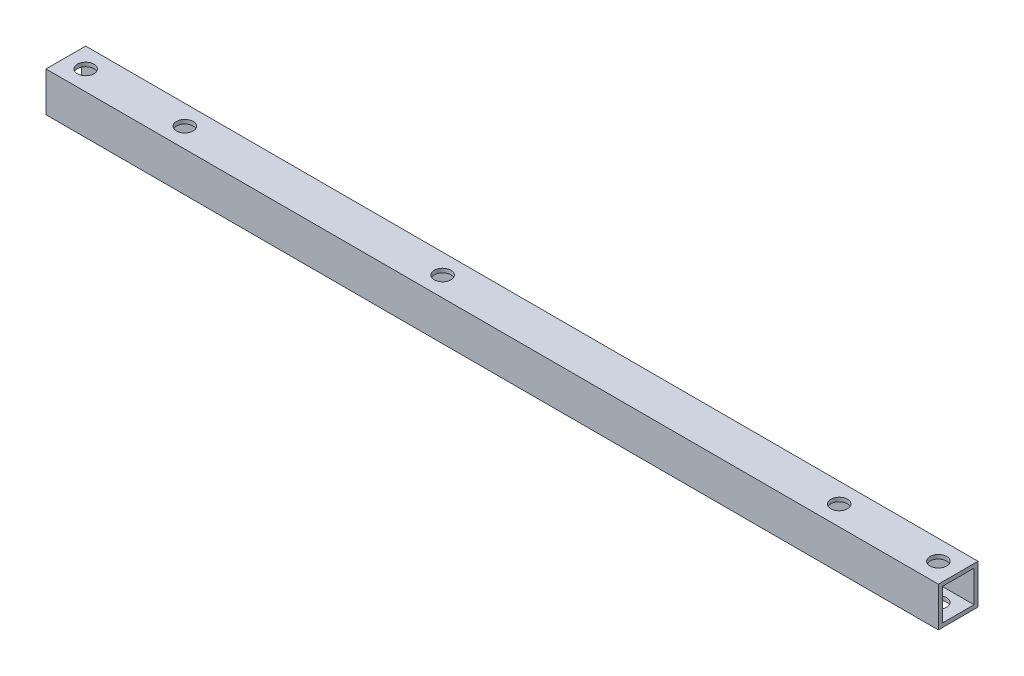
SolidWorks part; units mm, degrees
material "5052-H34"
ref_plane "正面" through (0, 0, 0) normal (0, 0, 1) x (1, 0, 0)
ref_plane "平面" through (0, 0, 0) normal (0, 1, 0) x (1, 0, 0)
ref_plane "右側面" through (0, 0, 0) normal (1, 0, 0) x (0, 0, -1)
sketch "ｽｹｯﾁ1" plane through (0, 0, 0) normal (1, 0, 0) x (0, 0, -1)
  line L1 (-5, 5) -> (5, 5)
  line L2 (-5, 5) -> (-5, -5)
  line L3 (-5, -5) -> (5, -5)
  line L4 (5, 5) -> (5, -5)
  line L5 (-5, 5) -> (5, -5) construction
  line L6 (-5, -5) -> (5, 5) construction
  point P0 (0, 0)
  dimension "D1" = 10
extrude "押し出し-薄板1" add sketch "ｽｹｯﾁ1" along normal blind 225 thin
sketch "ｽｹｯﾁ2" plane through (0, 5, 0) normal (0, 1, 0) x (1, 0, 0)
  line L0 (225, 0) -> (195, 0) construction
  line L1 (225, 5) -> (225, -5) construction
  line L2 (112.5, 5) -> (112.5, -5) construction
  line L3 (225, 5) -> (0, 5) construction
  line L4 (225, -5) -> (0, -5) construction
  line L5 (0, 0) -> (30, 0) construction
  circle A0 centre (195, 0) radius 2.1
  circle A1 centre (220, 0) radius 2.1
  circle A2 centre (5, 0) radius 2.1
  circle A3 centre (30, 0) radius 2.1
  dimension "D1" = 4.2
  dimension "D2" = 25
  dimension "D3" = 5
extrude "ｶｯﾄ - 押し出し1" cut sketch "ｽｹｯﾁ2" against normal through all
sketch "ｽｹｯﾁ3" plane through (0, 5, 0) normal (0, 1, 0) x (1, 0, 0)
  line L0 (0, 0) -> (95, 0) construction
  circle A0 centre (95, 0) radius 2.1
  dimension "D1" = 4.2
  dimension "D2" = 95
extrude "ｶｯﾄ - 押し出し2" cut sketch "ｽｹｯﾁ3" against normal through all
